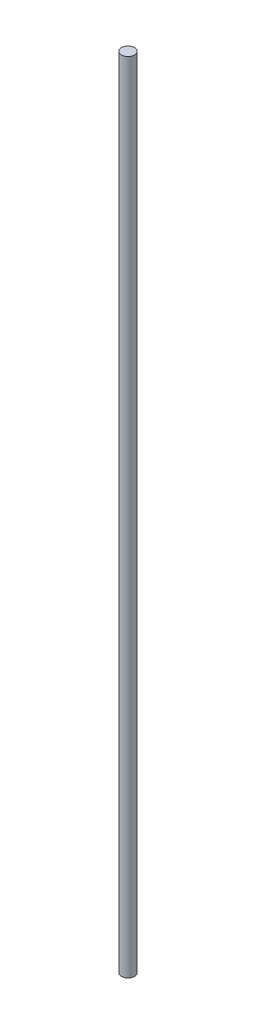
SolidWorks part; units mm, degrees
material "AISI Type A2 Tool Steel"
ref_plane "Front Plane" through (0, 0, 0) normal (0, 0, 1) x (1, 0, 0)
ref_plane "Top Plane" through (0, 0, 0) normal (0, 1, 0) x (1, 0, 0)
ref_plane "Right Plane" through (0, 0, 0) normal (1, 0, 0) x (0, 0, -1)
sketch "Sketch1" plane through (0, 0, 0) normal (0, 1, 0) x (1, 0, 0)
  circle A0 centre (0, 0) radius 2.65
  dimension "D1" = 5.3
extrude "Boss-Extrude1" add sketch "Sketch1" along normal blind 326
